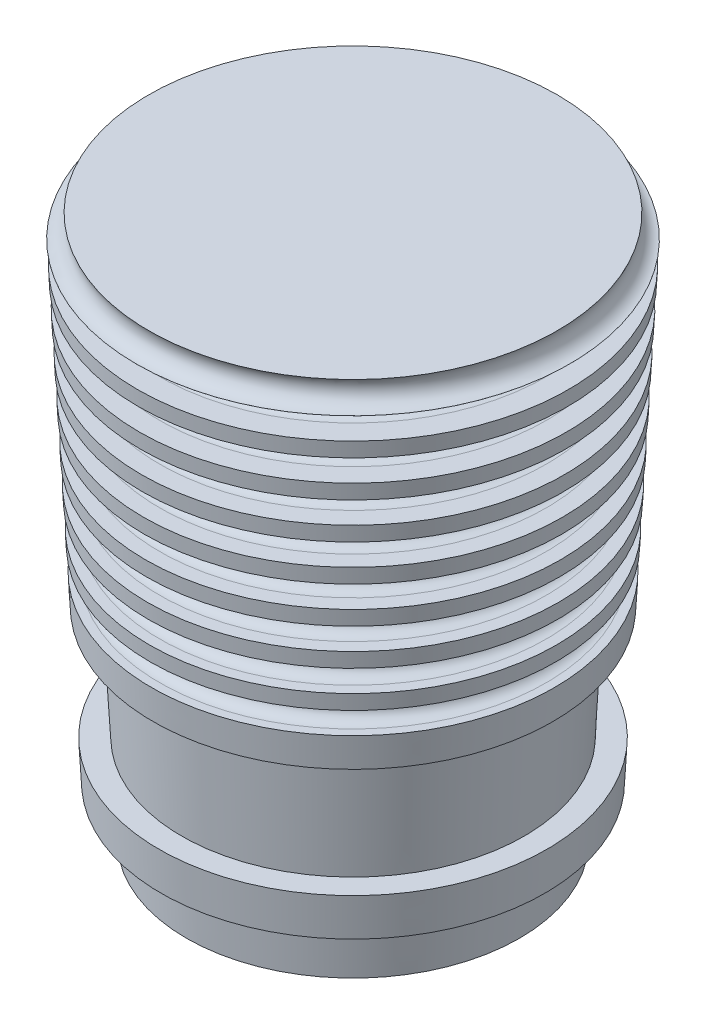
SolidWorks part; units mm, degrees
ref_plane "Front Plane" through (0, 0, 0) normal (0, 0, 1) x (1, 0, 0)
ref_plane "Top Plane" through (0, 0, 0) normal (0, 1, 0) x (1, 0, 0)
ref_plane "Right Plane" through (0, 0, 0) normal (1, 0, 0) x (0, 0, -1)
sketch "Sketch1" plane through (0, 0, 0) normal (0, 1, 0) x (1, 0, 0)
  circle A0 centre (0, 0) radius 25
  dimension "D1" = 50
extrude "Boss-Extrude1" add sketch "Sketch1" along normal blind 72 draft 3 draft outward yes
sketch "Sketch3" plane through (0, 0, 0) normal (0, 0, 1) x (1, 0, 0)
  line L0 (22.3664, 6.9904) -> (22, 0)
  line L1 (22, 0) -> (25, 0)
  line L2 (25, 0) -> (28.7734, 72) construction
  line L3 (25, 0) -> (25.3581, 6.8336)
  line L4 (25.3581, 6.8336) -> (22.3664, 6.9904)
  line L5 (23.415, 27) -> (22.6289, 12)
  line L6 (22.6289, 12) -> (25.6289, 12)
  line L7 (25.6289, 12) -> (26.415, 27)
  line L8 (26.415, 27) -> (23.415, 27)
  line L10 (-25, 0) -> (25, 0) construction
  line L11 (0, 0) -> (0, 55.205) construction
  dimension "D1" = 27
  dimension "D2" = 7
  dimension "D3" = 15
  dimension "D4" = 3
revolve "Cut-Revolve1" cut sketch "Sketch3" angle 360 about L11
sketch "Sketch4" plane through (0, 0, 0) normal (1, 0, 0) x (0, 0, -1)
  line L0 (25.5334, 69) -> (28.6161, 69)
  line L1 (26.415, 27) -> (28.7734, 72) construction
  line L2 (28.6161, 69) -> (28.4589, 66)
  line L3 (28.4589, 66) -> (25.5334, 66)
  line L4 (28.7734, 72) -> (-28.7734, 72) construction
  line L5 (0, 0) -> (0, 112.482) construction
  arc A0 (25.5334, 69) -> (25.5334, 66) centre (25.5334, 67.5) ccw
  dimension "D1" = 3
  dimension "D2" = 3
  dimension "D3" = 3
revolve "Cut-Revolve2" cut sketch "Sketch4" angle 360 about L5
pattern_linear "LPattern1" count 8 spacing 5 along (0, -1, 0) of "Cut-Revolve2"
sketch "Sketch5" plane through (0, 0, 0) normal (0, 0, 1) x (1, 0, 0)
  line L0 (28.6161, 69) -> (28.7734, 72) construction
  line L1 (-28.6161, 69) -> (28.6161, 69) construction
  line L2 (0, 0) -> (0, 91.8833) construction
  line L3 (-22, 0) -> (22, 0) construction
  circle A0 centre (28.721, 71) radius 2
  dimension "D1" = 4
revolve "Cut-Revolve3" cut sketch "Sketch5" angle 360 about L2
